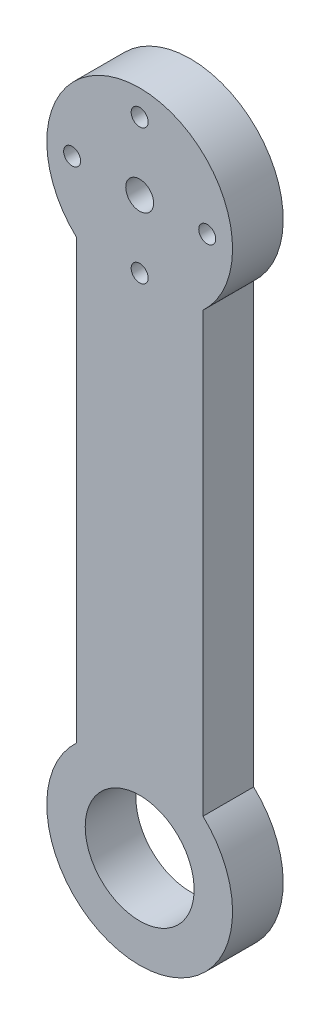
SolidWorks part; units mm, degrees
ref_plane "Plan de face" through (0, 0, 0) normal (0, 0, 1) x (1, 0, 0)
ref_plane "Plan de dessus" through (0, 0, 0) normal (0, 1, 0) x (1, 0, 0)
ref_plane "Plan de droite" through (0, 0, 0) normal (1, 0, 0) x (0, 0, -1)
sketch "Esquisse1" plane through (0, 0, 0) normal (0, 0, 1) x (1, 0, 0)
  line L1 (0, 0) -> (15, 0)
  line L2 (0, 0) -> (0, 83)
  line L3 (0, 83) -> (15, 83)
  line L4 (15, 0) -> (15, 83)
  dimension "D1" = 83
  dimension "D2" = 15
extrude "Boss.-Extru.1" add sketch "Esquisse1" along normal blind 6
sketch "Esquisse2" plane through (0, 0, 6) normal (0, 0, 1) x (1, 0, 0)
  line L0 (15, 0) -> (15, 83) construction
  line L1 (0, 0) -> (15, 0) construction
  line L2 (15, 83) -> (0, 83) construction
  line L3 (15, 0) -> (15, 83) construction
  circle A0 centre (7.5, 7.5) radius 11
  circle A1 centre (7.5, 75.5) radius 11
  dimension "D2" = 22
  dimension "D5" = 22
  dimension "D1" = 7.5
  dimension "D3" = 7.5
  dimension "D4" = 7.5
  dimension "D6" = 7.5
extrude "Boss.-Extru.2" add sketch "Esquisse2" against normal blind 6
sketch "Esquisse4" plane through (0, 0, 0) normal (0, 0, -1) x (-1, 0, 0)
  line L0 (-7.5, 86.5) -> (-7.5, 107.232) construction
  line L1 (-18.5, 75.5) -> (3.5, 75.5) construction
  circle A0 centre (-7.5, 75.5) radius 1.65
  circle A1 centre (-7.5, 67.5) radius 1.005
  circle A2 centre (-15.5, 75.5) radius 1.005
  circle A3 centre (-7.5, 83.5) radius 1.005
  circle A4 centre (0.5, 75.5) radius 1.005
  arc A5 (0, 67.4533) -> (-15, 67.4533) centre (-7.5, 75.5) ccw construction
  circle A6 centre (-7.5, 7.5) radius 6.45
  dimension "D1" = 3.3
  dimension "D2" = 8
  dimension "D3" = 8
  dimension "D4" = 8
  dimension "D6" = 2.01
  dimension "D7" = 2.01
  dimension "D8" = 2.01
  dimension "D9" = 2.01
  dimension "D10" = 12.9
  dimension "D5" = 8
extrude "Enlèv. mat.-Extru.2" cut sketch "Esquisse4" against normal blind 10
sketch "Esquisse5" plane through (0, 0, 0) normal (0, 0, -1) x (-1, 0, 0)
  circle A0 centre (-7.5, 75.5) radius 3
  circle A1 centre (-15.5, 75.5) radius 2
  circle A2 centre (-7.5, 83.5) radius 2
  circle A3 centre (0.5, 75.5) radius 2
  circle A4 centre (-7.5, 67.5) radius 2
  dimension "D1" = 6
  dimension "D2" = 4
  dimension "D3" = 4
  dimension "D4" = 4
  dimension "D5" = 4
extrude "Enlèv. mat.-Extru.3" cut sketch "Esquisse5" against normal blind 3
